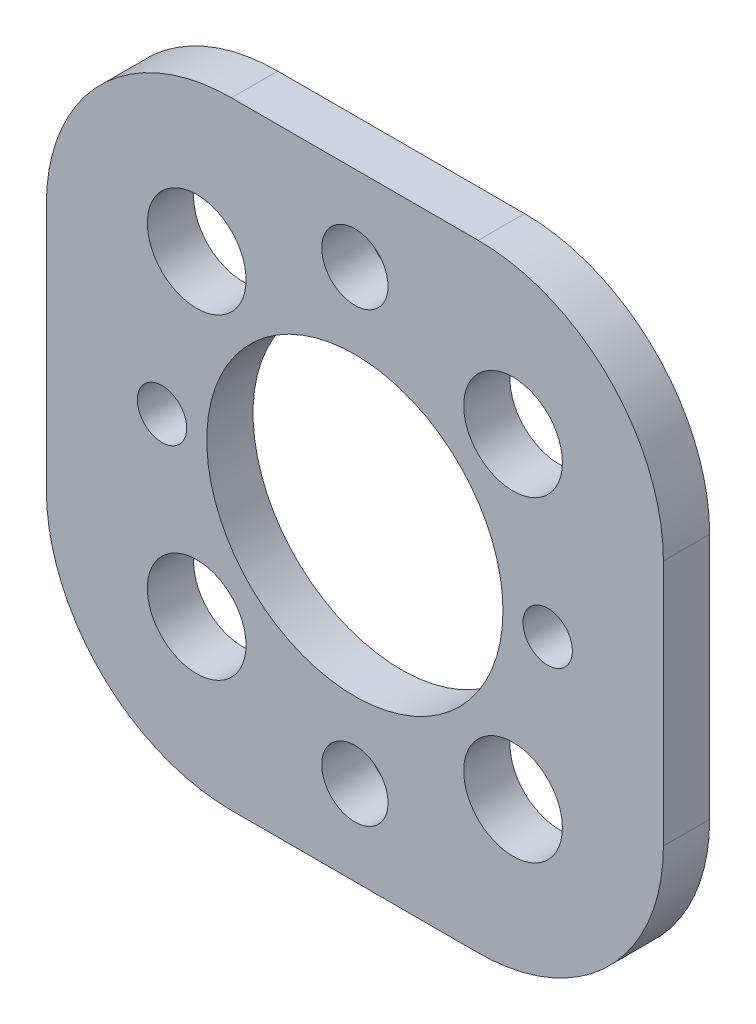
SolidWorks part; units mm, degrees
material "6061-T6 (SS)"
ref_plane "Front" through (0, 0, 0) normal (0, 0, 1) x (1, 0, 0)
ref_plane "Top" through (0, 0, 0) normal (0, 1, 0) x (1, 0, 0)
ref_plane "Right" through (0, 0, 0) normal (1, 0, 0) x (0, 0, -1)
sketch "Sketch1" plane through (0, 0, 0) normal (0, 0, 1) x (1, 0, 0)
  line L1 (8, -20) -> (-8, -20)
  line L2 (20, -8) -> (20, 8)
  line L3 (8, 20) -> (-8, 20)
  line L4 (-20, -8) -> (-20, 8)
  line L5 (20, -20) -> (-20, 20) construction
  line L6 (20, 20) -> (-20, -20) construction
  circle A0 centre (0, 0) radius 9.6
  circle A1 centre (0, 0) radius 12.5 construction
  circle A2 centre (0, 0) radius 14.5 construction
  circle A3 centre (0, 14.5) radius 2.15
  circle A4 centre (-12.5, 0) radius 1.6
  circle A5 centre (12.5, 0) radius 1.6
  circle A6 centre (0, -14.5) radius 2.15
  circle A7 centre (10.253, 10.253) radius 3.2
  arc A8 (-8, -20) -> (-20, -8) centre (-8, -8) cw
  arc A9 (8, -20) -> (20, -8) centre (8, -8) ccw
  arc A10 (20, 8) -> (8, 20) centre (8, 8) ccw
  arc A11 (-8, 20) -> (-20, 8) centre (-8, 8) ccw
  circle A12 centre (10.253, -10.253) radius 3.2
  circle A13 centre (-10.253, -10.253) radius 3.2
  circle A14 centre (-10.253, 10.253) radius 3.2
  point P40 (0, 0)
  dimension "D1" = 19.2
  dimension "D2" = 29
  dimension "D3" = 25
  dimension "D4" = 4.3
  dimension "D5" = 3.2
  dimension "D6" = 6.4
  dimension "D8" = 12
  dimension "D7" = 40
  dimension "D9" = 4
extrude "Boss-Extrude1" add sketch "Sketch1" along normal blind 3
